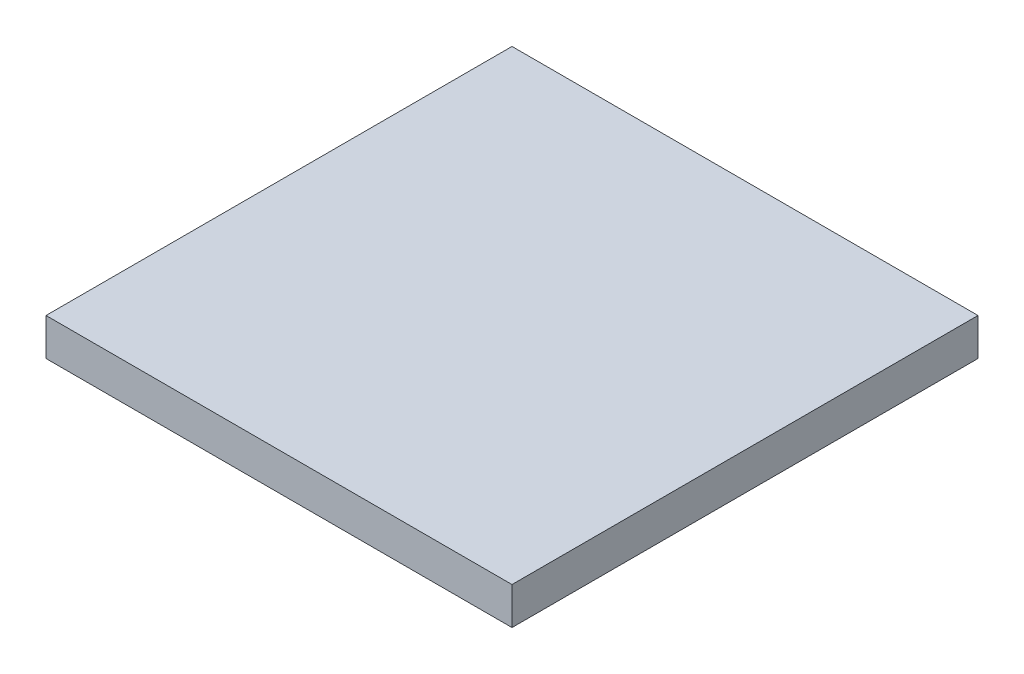
SolidWorks part; units mm, degrees
material "Balsa"
ref_plane "Front Plane" through (0, 0, 0) normal (0, 0, 1) x (1, 0, 0)
ref_plane "Top Plane" through (0, 0, 0) normal (0, 1, 0) x (1, 0, 0)
ref_plane "Right Plane" through (0, 0, 0) normal (1, 0, 0) x (0, 0, -1)
sketch "Sketch2" plane through (0, 0, 0) normal (0, 1, 0) x (1, 0, 0)
  line L1 (0, 0) -> (37.5, 0)
  line L2 (0, 0) -> (0, 37.5)
  line L3 (0, 37.5) -> (37.5, 37.5)
  line L4 (37.5, 0) -> (37.5, 37.5)
  dimension "D1" = 37.5
  dimension "D2" = 37.5
extrude "Boss-Extrude1" add sketch "Sketch2" along normal blind 3
